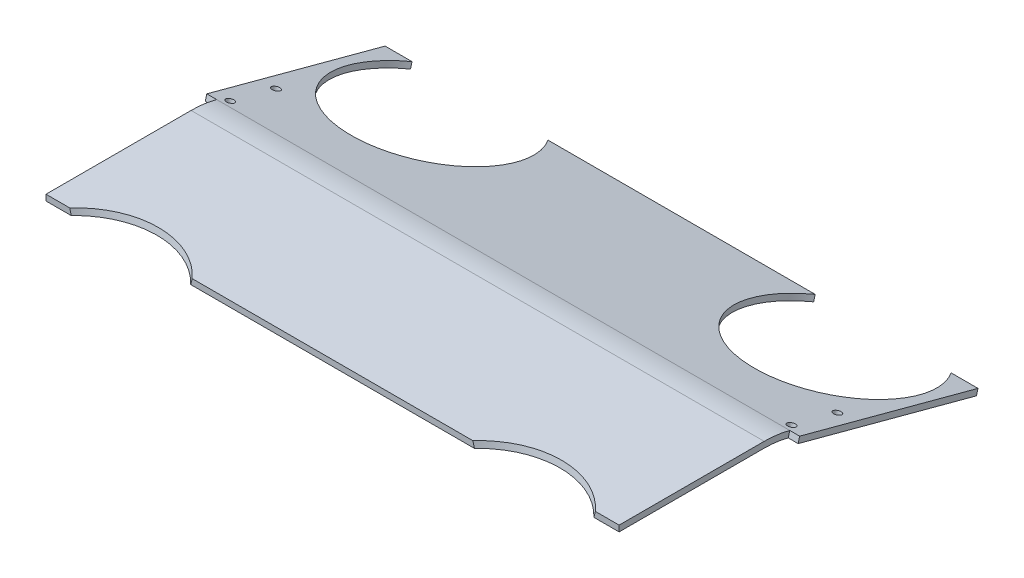
SolidWorks part; units mm, degrees
material "PMMA"
ref_plane "前视基准面" through (0, 0, 0) normal (0, 0, 1) x (1, 0, 0)
ref_plane "上视基准面" through (0, 0, 0) normal (0, 1, 0) x (1, 0, 0)
ref_plane "右视基准面" through (0, 0, 0) normal (1, 0, 0) x (0, 0, -1)
sketch "Sketch1" plane through (0, 0, 0) normal (1, 0, 0) x (0, 0, -1)
  line L0 (0, 0) -> (73.4174, 0)
  line L1 (86.3583, -1.7037) -> (176.5926, -25.8819)
  line L2 (0, -3) -> (73.4174, -3)
  line L3 (85.5819, -4.6015) -> (175.8161, -28.7797)
  line L4 (0, 0) -> (0, -3)
  line L5 (176.5926, -25.8819) -> (175.8161, -28.7797)
  arc A0 (73.4174, 0) -> (86.3583, -1.7037) centre (73.4174, -50) cw
  arc A1 (73.4174, -3) -> (85.5819, -4.6015) centre (73.4174, -50) cw
  point P6 (80, 0)
  dimension "D4" = 50
  dimension "D1" = 80
  dimension "D2" = 100
  dimension "D3" = 165
  dimension "D5" = 3
extrude "Boss-Extrude1" add sketch "Sketch1" along normal blind 300
sketch "Sketch2" plane through (0, 20, -5.359) normal (0, 0.9659, -0.2588) x (1, 0, 0)
  line L0 (300, 177.2741) -> (0, 177.2741) construction
  line L1 (0, 177.2741) -> (0, 83.8567) construction
  line L2 (150, 187.5808) -> (150, -17.0827) construction
  line L3 (0, 70.9157) -> (0, 0) construction
  line L4 (0, 83.8567) -> (5, 83.8567)
  line L5 (300, 83.8567) -> (0, 83.8567) construction
  line L6 (5, 83.8567) -> (5, 0)
  line L7 (300, 0) -> (0, 0) construction
  line L8 (5, 0) -> (0, 0)
  line L9 (0, 0) -> (0, 83.8567)
  line L10 (295, 0) -> (300, 0)
  line L11 (295, 83.8567) -> (295, 0)
  line L12 (300, 83.8567) -> (295, 83.8567)
  line L13 (300, 0) -> (300, 83.8567)
  line L14 (48, 225.6616) -> (48, -53.1429) construction
  line L15 (300, 70.9157) -> (0, 70.9157) construction
  circle A0 centre (48, 152.2741) radius 42.5
  circle A1 centre (252, 152.2741) radius 42.5
  circle A2 centre (48, -29.0843) radius 42.5
  circle A3 centre (252, -29.0843) radius 42.5
  dimension "D1" = 85
  dimension "D6" = 85
  dimension "D2" = 25
  dimension "D3" = 48
  dimension "D4" = 150
  dimension "D5" = 5
  dimension "D7" = 100
extrude "Cut-Extrude1" cut sketch "Sketch2" against normal through all
sketch "Sketch3" plane through (0, 20, -5.359) normal (0, 0.9659, -0.2588) x (1, 0, 0)
  line L0 (0, 186.0553) -> (0, 75.4061) construction
  line L1 (150, 191.3664) -> (150, -11.933) construction
  line L2 (5, 70.9157) -> (5, 0) construction
  line L3 (8, 186.0553) -> (8, 75.4061) construction
  line L4 (295, 83.8567) -> (5, 83.8567) construction
  circle A0 centre (8, 87.8567) radius 2
  circle A1 centre (8, 111.8567) radius 2
  circle A2 centre (292, 87.8567) radius 2
  circle A3 centre (292, 111.8567) radius 2
  dimension "D3" = 4
  dimension "D4" = 4
  dimension "D1" = 145
  dimension "D5" = 24
  dimension "D6" = 4
  dimension "D2" = 8
extrude "Cut-Extrude2" cut sketch "Sketch3" against normal through all
